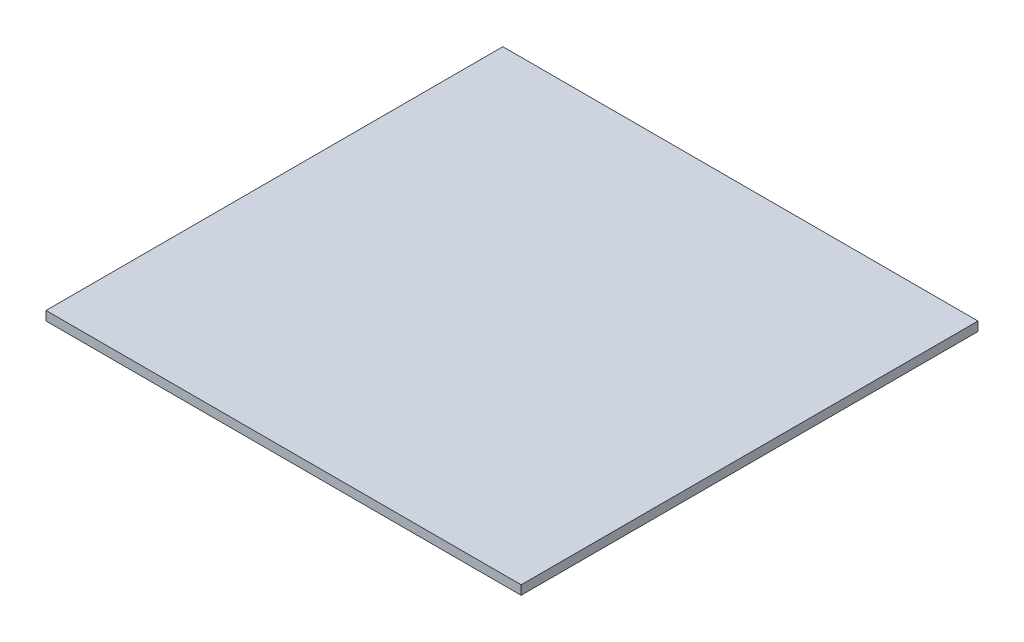
SolidWorks part; units mm, degrees
ref_plane "Plan de face" through (0, 0, 0) normal (0, 0, 1) x (1, 0, 0)
ref_plane "Plan de dessus" through (0, 0, 0) normal (0, 1, 0) x (1, 0, 0)
ref_plane "Plan de droite" through (0, 0, 0) normal (1, 0, 0) x (0, 0, -1)
sketch "Esquisse1" plane through (0, 0, 0) normal (0, 1, 0) x (1, 0, 0)
  line L1 (0, 0) -> (260, 0)
  line L2 (0, 0) -> (0, 250)
  line L3 (0, 250) -> (260, 250)
  line L4 (260, 0) -> (260, 250)
  dimension "D1" = 260
  dimension "D2" = 250
extrude "Boss.-Extru.2" add sketch "Esquisse1" along normal blind 5
